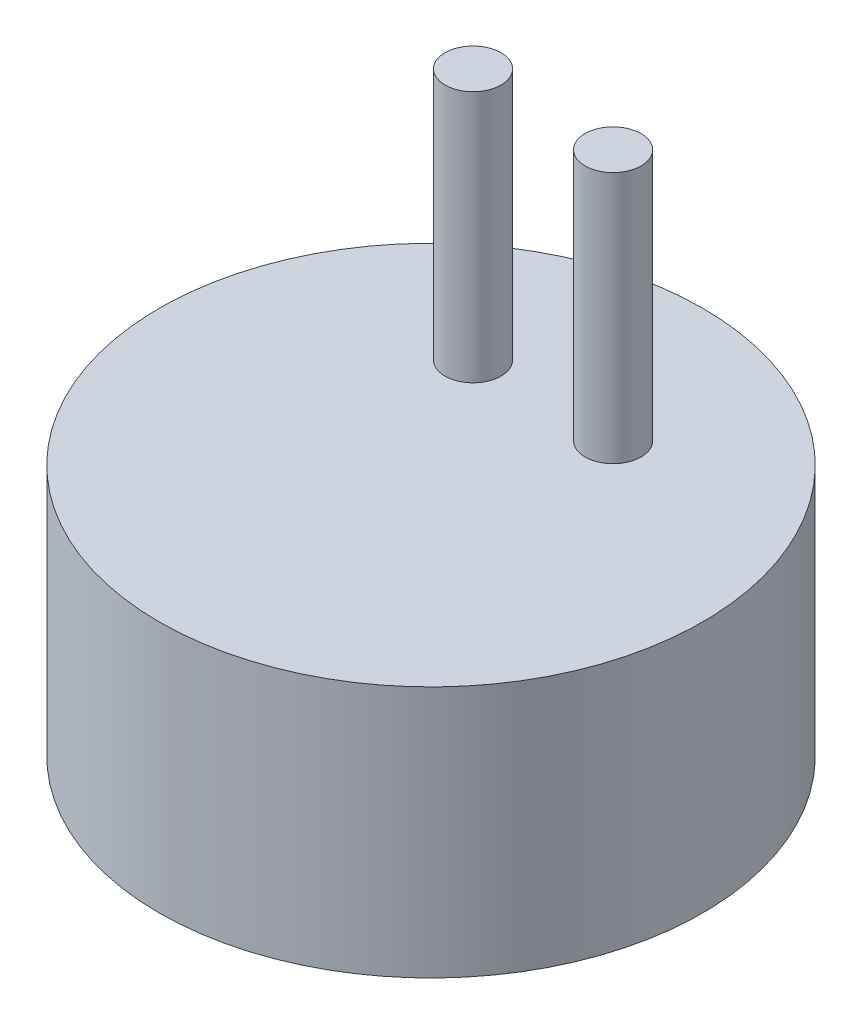
SolidWorks part; units mm, degrees
ref_plane "Front" through (0, 0, 0) normal (0, 0, 1) x (1, 0, 0)
ref_plane "Top" through (0, 0, 0) normal (0, 1, 0) x (1, 0, 0)
ref_plane "Right" through (0, 0, 0) normal (1, 0, 0) x (0, 0, -1)
sketch "스케치1" plane through (0, 0, 0) normal (0, 1, 0) x (1, 0, 0)
  circle A0 centre (0, 0) radius 4.85
extrude "보스-돌출1" add sketch "스케치1" along normal blind 4.5
sketch "스케치2" plane through (0, 4.5, 0) normal (0, 1, 0) x (1, 0, 0)
  line L0 (0, 0) -> (0, 2) construction
  line L1 (-4.4184, 2) -> (4.4184, 2) construction
  circle A0 centre (0, 0) radius 4.85 construction
  circle A2 centre (1.25, 2) radius 0.5
  circle A3 centre (-1.25, 2) radius 0.5
extrude "보스-돌출3" add sketch "스케치2" along normal blind 4.5
